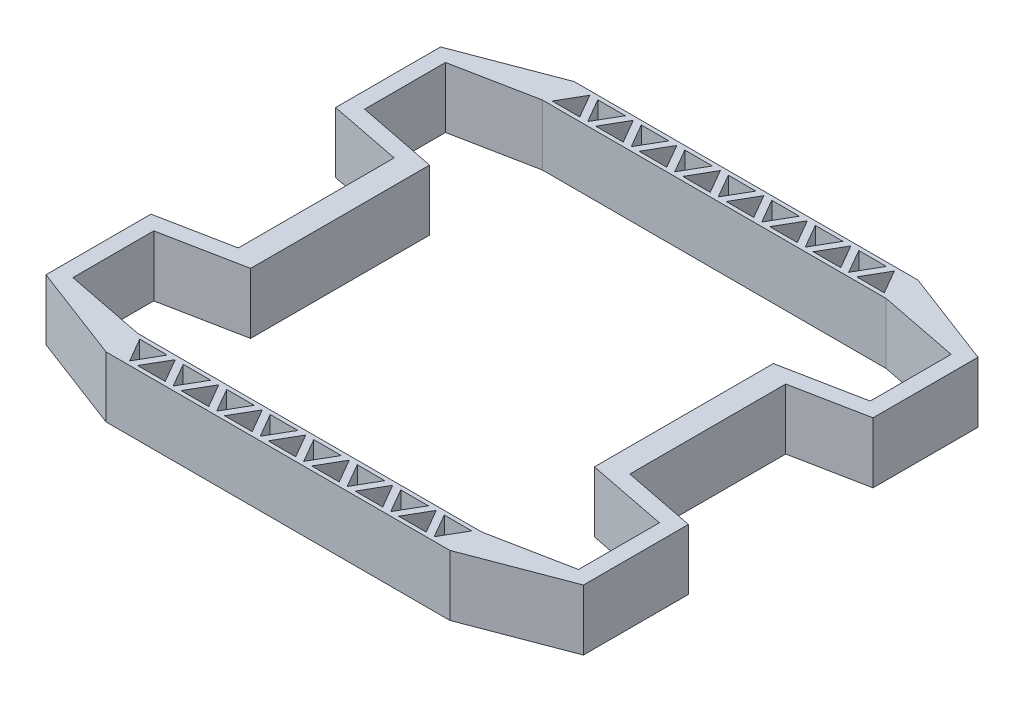
SolidWorks part; units mm, degrees
ref_plane "Front Plane" through (0, 0, 0) normal (0, 0, 1) x (1, 0, 0)
ref_plane "Top Plane" through (0, 0, 0) normal (0, 1, 0) x (1, 0, 0)
ref_plane "Right Plane" through (0, 0, 0) normal (1, 0, 0) x (0, 0, -1)
sketch "Sketch1" plane through (0, 0, 0) normal (0, 1, 0) x (1, 0, 0)
  line L0 (107.95, 274) -> (0, 274)
  line L1 (0, 0) -> (107.95, 0)
  line L2 (0, 0) -> (0, 254)
  line L3 (0, 254) -> (107.95, 254)
  line L4 (107.95, 0) -> (107.95, 254) construction
  line L5 (-15, 127) -> (0, 127)
  line L6 (-60.8, 250.8919) -> (-60.8, 184.9721)
  line L7 (-15, 175.9515) -> (-15, 127)
  line L8 (-60.8, 184.9721) -> (-15, 175.9515)
  line L9 (-60.8, 217.932) -> (0, 217.932) construction
  line L11 (0, 254) -> (0, 274)
  line L12 (-50.8, 243.9947) -> (0, 254)
  line L13 (-50.8, 243.9947) -> (-50.8, 193.1947)
  line L14 (-50.8, 193.1947) -> (0, 183.1893)
  line L16 (107.95, 264) -> (1.8363, 264) construction
  line L17 (1.8363, 264) -> (-50.8, 243.9947) construction
  line L18 (0, 274) -> (-60.8, 250.8919) construction
  line L19 (-60.8, 250.8919) -> (0, 274)
  line L20 (3.668, 256.5) -> (12.3282, 271.5)
  line L21 (12.3282, 271.5) -> (20.9885, 256.5)
  line L22 (20.9885, 256.5) -> (3.668, 256.5)
  line L23 (7.9981, 264) -> (16.6583, 264) construction
  line L24 (44.6487, 271.5) -> (61.9692, 271.5)
  line L26 (30.3186, 264) -> (21.6583, 264) construction
  line L29 (17.3282, 271.5) -> (34.6487, 271.5)
  line L30 (34.6487, 271.5) -> (25.9885, 256.5)
  line L31 (25.9885, 256.5) -> (17.3282, 271.5)
  line L32 (61.9692, 271.5) -> (53.309, 256.5)
  line L33 (53.309, 256.5) -> (44.6487, 271.5)
  line L34 (48.309, 256.5) -> (30.9885, 256.5)
  line L35 (30.9885, 256.5) -> (39.6487, 271.5)
  line L36 (39.6487, 271.5) -> (48.309, 256.5)
  line L37 (71.9692, 271.5) -> (89.2897, 271.5)
  line L38 (89.2897, 271.5) -> (80.6295, 256.5)
  line L39 (80.6295, 256.5) -> (71.9692, 271.5)
  line L40 (75.6295, 256.5) -> (58.309, 256.5)
  line L41 (58.309, 256.5) -> (66.9692, 271.5)
  line L42 (66.9692, 271.5) -> (75.6295, 256.5)
  line L43 (99.2897, 271.5) -> (107.95, 271.5)
  line L45 (107.95, 256.5) -> (99.2897, 271.5)
  line L46 (102.95, 256.5) -> (85.6295, 256.5)
  line L47 (85.6295, 256.5) -> (94.2897, 271.5)
  line L48 (94.2897, 271.5) -> (102.95, 256.5)
  line L50 (107.95, 254) -> (107.95, 256.5)
  line L51 (116.6103, 271.5) -> (107.95, 256.5) [skipped]
  line L52 (0, 183.1893) -> (-13.2727, 157.5197) construction
  line L53 (107.95, 271.5) -> (107.95, 274)
  line L54 (-15, 175.9515) -> (-22.1555, 162.1126) construction
  dimension "D1" = 107.95
  dimension "D2" = 254
  dimension "D3" = 20
  dimension "D4" = 36.068
  dimension "D5" = 15
  dimension "D6" = 60.8
  dimension "D8" = 50.8
  dimension "D10" = 15
  dimension "D11" = 7.5
  dimension "D12" = 5
  dimension "D13" = 7.5
  dimension "D15" = 5
  dimension "D7" = 10
  dimension "D14" = 4
extrude "Boss-Extrude1" add sketch "Sketch1" along normal blind 38.1
mirror "Mirror1" about plane through (0, 38.1, -127) normal (0, 0, -1) of bodies 101
mirror "Mirror2" about plane through (107.95, 38.1, -254) normal (-1, 0, 0) of bodies 102
